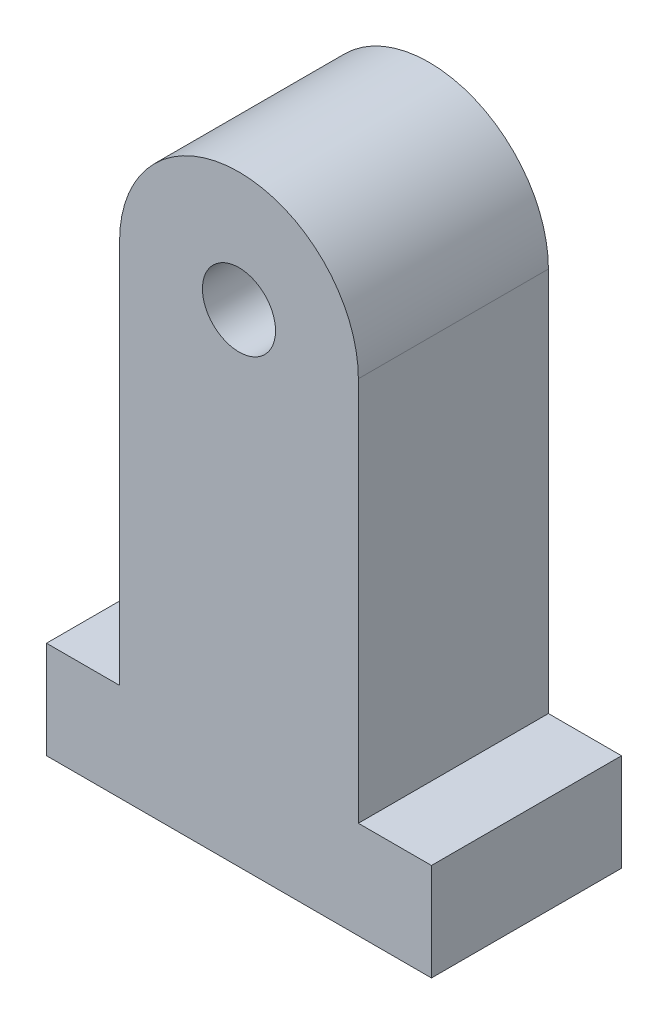
SolidWorks part; units mm, degrees
ref_plane "Front Plane" through (0, 0, 0) normal (0, 0, 1) x (1, 0, 0)
ref_plane "Top Plane" through (0, 0, 0) normal (0, 1, 0) x (1, 0, 0)
ref_plane "Right Plane" through (0, 0, 0) normal (1, 0, 0) x (0, 0, -1)
sketch "Sketch1" plane through (0, 0, 0) normal (0, 0, 1) x (1, 0, 0)
  line L0 (10.033, 0) -> (-10.033, 0)
  line L1 (-10.033, 0) -> (-10.033, 5.08)
  line L2 (-10.033, 5.08) -> (-6.223, 5.08)
  line L3 (-6.223, 5.08) -> (-6.223, 25.146)
  line L4 (0, 0) -> (0, 25.146) construction
  line L5 (10.033, 0) -> (10.033, 5.08)
  line L6 (10.033, 5.08) -> (6.223, 5.08)
  line L7 (6.223, 5.08) -> (6.223, 25.146)
  circle A0 centre (0, 25.146) radius 1.905
  arc A2 (-6.223, 25.146) -> (6.223, 25.146) centre (0, 25.146) cw
  dimension "D1" = 3.81
  dimension "D2" = 6.223
  dimension "D3" = 3.81
  dimension "D4" = 25.146
  dimension "D5" = 5.08
extrude "Boss-Extrude1" add sketch "Sketch1" along normal mid plane 9.906
